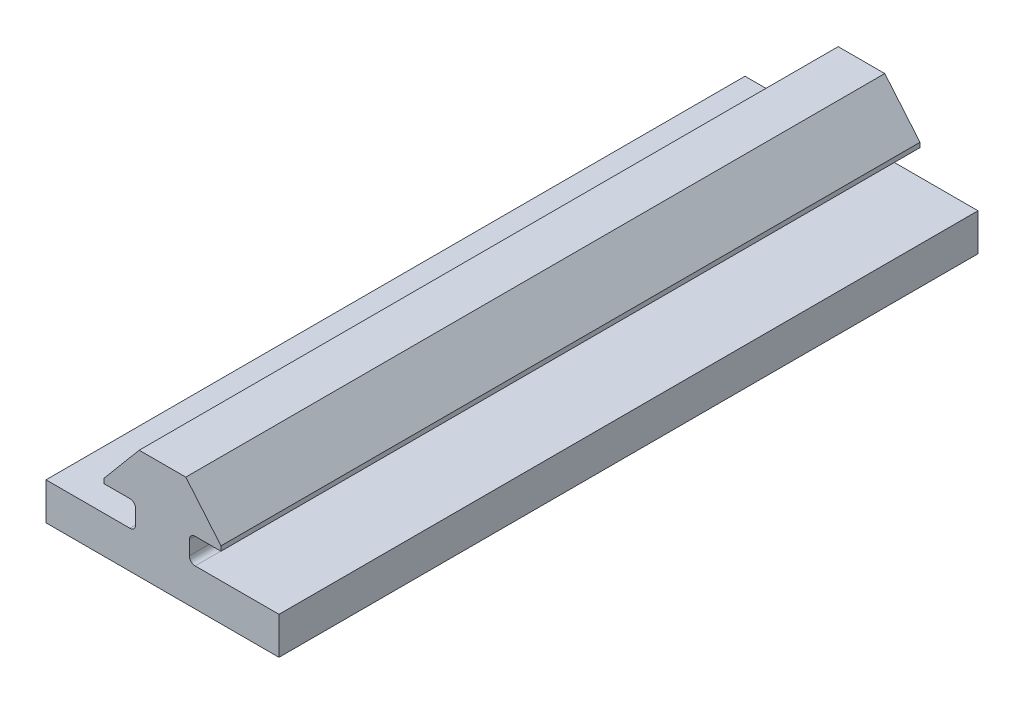
SolidWorks part; units mm, degrees
ref_plane "Front Plane" through (0, 0, 0) normal (0, 0, 1) x (1, 0, 0)
ref_plane "Top Plane" through (0, 0, 0) normal (0, 1, 0) x (1, 0, 0)
ref_plane "Right Plane" through (0, 0, 0) normal (1, 0, 0) x (0, 0, -1)
ref_plane "Plane1" through (0, 0, -3683) normal (0, 0, -1) x (-1, 0, 0)
sketch "Sketch1" plane through (0, 0, -3683) normal (0, 0, -1) x (-1, 0, 0)
  line L0 (12.7, 4.064) -> (3.556, 4.064)
  line L1 (2.921, 4.699) -> (2.921, 6.223)
  line L2 (3.556, 6.858) -> (6.3764, 6.858)
  line L3 (6.3764, 6.858) -> (6.3764, 7.366)
  line L4 (6.3764, 7.366) -> (2.54, 11.938)
  line L5 (2.54, 11.938) -> (-2.54, 11.938)
  line L6 (-2.54, 11.938) -> (-6.3764, 7.366)
  line L7 (-6.3764, 7.366) -> (-6.3764, 6.858)
  line L8 (-6.3764, 6.858) -> (-3.556, 6.858)
  line L9 (-2.921, 6.223) -> (-2.921, 4.699)
  line L10 (-3.556, 4.064) -> (-12.7, 4.064)
  line L11 (-12.7, 4.064) -> (-12.7, 0)
  line L12 (-12.7, 0) -> (12.7, 0)
  line L13 (12.7, 0) -> (12.7, 4.064)
  arc A0 (3.556, 4.064) -> (2.921, 4.699) centre (3.556, 4.699) cw
  arc A1 (2.921, 6.223) -> (3.556, 6.858) centre (3.556, 6.223) cw
  arc A2 (-3.556, 6.858) -> (-2.921, 6.223) centre (-3.556, 6.223) cw
  arc A3 (-2.921, 4.699) -> (-3.556, 4.064) centre (-3.556, 4.699) cw
extrude "Boss-Extrude6" add sketch "Sketch1" along normal blind 76.2
